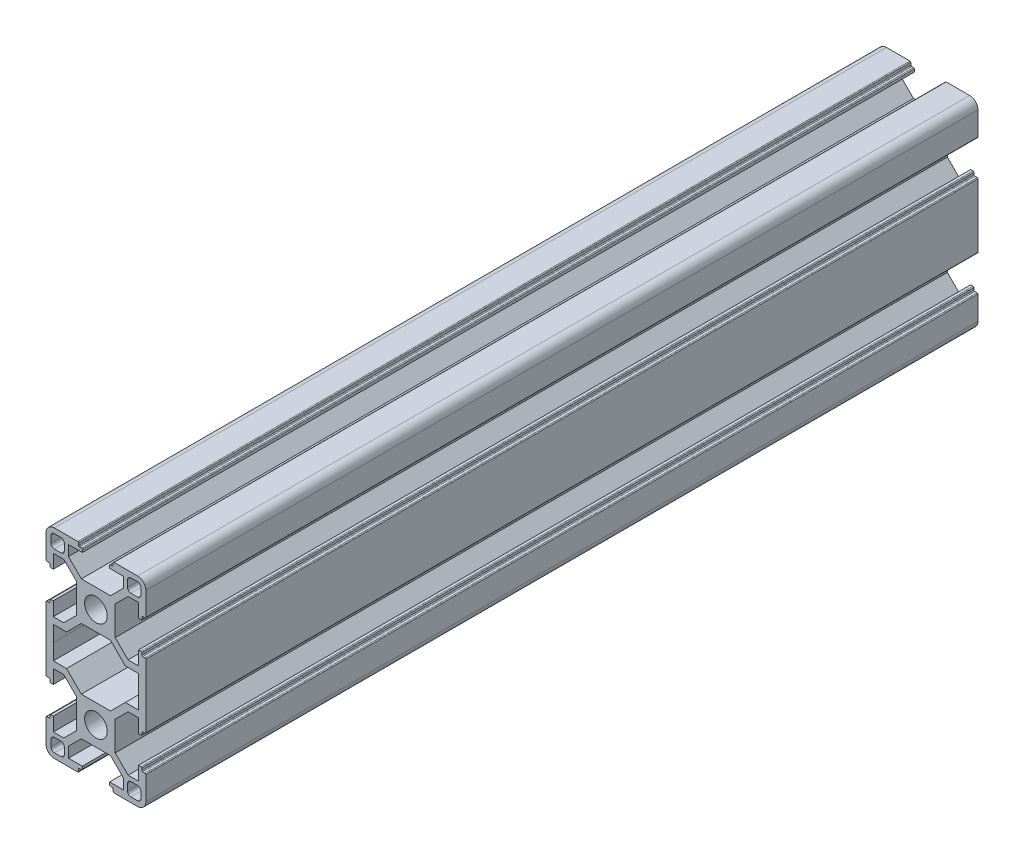
SolidWorks part; units mm, degrees
ref_plane "Front Plane" through (0, 0, 0) normal (0, 0, 1) x (1, 0, 0)
ref_plane "Top Plane" through (0, 0, 0) normal (0, 1, 0) x (1, 0, 0)
ref_plane "Right Plane" through (0, 0, 0) normal (1, 0, 0) x (0, 0, -1)
sketch "Sketch1" plane through (0, 0, 0) normal (0, 0, 1) x (1, 0, 0)
  line L0 (0, -5.8) -> (0, 5.8) construction
  line L1 (0, 0) -> (-15, 15) construction
  line L2 (-15, 15) -> (-5.2, 15)
  line L3 (-5.2, 15) -> (-5.2, 13.8083)
  line L4 (-5.2, 13.8083) -> (-4.1, 13.8083)
  line L5 (-4.1, 13.8083) -> (-4.1, 12.8)
  line L6 (-4.1, 12.8) -> (-8.25, 12.8)
  line L7 (-8.25, 12.8) -> (-8.25, 9.6642)
  line L8 (-8.25, 9.6642) -> (-4.3858, 5.8)
  line L9 (-4.3858, 5.8) -> (4.3858, 5.8)
  line L10 (-5.8, 4.3858) -> (-5.8, -4.3858)
  line L11 (-9.6642, 8.25) -> (-5.8, 4.3858)
  line L12 (-12.8, 8.25) -> (-9.6642, 8.25)
  line L13 (-12.8, 4.1) -> (-12.8, 8.25)
  line L14 (-13.8083, 4.1) -> (-12.8, 4.1)
  line L15 (-13.8083, 5.2) -> (-13.8083, 4.1)
  line L16 (-15, 5.2) -> (-13.8083, 5.2)
  line L17 (-15, 15) -> (-15, 5.2)
  line L18 (0, 0) -> (15, 15) construction
  line L19 (15, 15) -> (15, 5.2)
  line L20 (15, 5.2) -> (13.8083, 5.2)
  line L21 (13.8083, 5.2) -> (13.8083, 4.1)
  line L22 (13.8083, 4.1) -> (12.8, 4.1)
  line L23 (12.8, 4.1) -> (12.8, 8.25)
  line L24 (12.8, 8.25) -> (9.6642, 8.25)
  line L25 (9.6642, 8.25) -> (5.8, 4.3858)
  line L26 (5.8, 4.3858) -> (5.8, -4.3858)
  line L27 (8.25, 9.6642) -> (4.3858, 5.8)
  line L28 (8.25, 12.8) -> (8.25, 9.6642)
  line L29 (4.1, 12.8) -> (8.25, 12.8)
  line L30 (4.1, 13.8083) -> (4.1, 12.8)
  line L31 (5.2, 13.8083) -> (4.1, 13.8083)
  line L32 (5.2, 15) -> (5.2, 13.8083)
  line L33 (15, 15) -> (5.2, 15)
  line L34 (0, 0) -> (3.5826, 0) construction
  line L35 (0, 0) -> (15, -15) construction
  line L36 (0, 0) -> (-15, -15) construction
  line L37 (-4.3858, -5.8) -> (-8.8358, -10.25)
  line L38 (-8.8358, -10.25) -> (-12.8, -10.25)
  line L39 (-12.8, -10.25) -> (-12.7618, -15)
  line L40 (-12.8, -19.75) -> (-12.7618, -15)
  line L41 (-8.8358, -19.75) -> (-12.8, -19.75)
  line L42 (-4.3858, -24.2) -> (-8.8358, -19.75)
  line L43 (4.3858, -5.8) -> (8.8358, -10.25)
  line L44 (9.6642, -8.25) -> (5.8, -4.3858)
  line L45 (12.8, -8.25) -> (9.6642, -8.25)
  line L46 (12.8, -4.1) -> (12.8, -8.25)
  line L47 (13.8083, -4.1) -> (12.8, -4.1)
  line L48 (13.8083, -5.2) -> (13.8083, -4.1)
  line L49 (15, -5.2) -> (13.8083, -5.2)
  line L50 (15, -24.8) -> (15, -5.2)
  line L51 (-15, -24.8) -> (-15, -5.2)
  line L52 (-15, -5.2) -> (-13.8083, -5.2)
  line L53 (-13.8083, -5.2) -> (-13.8083, -4.1)
  line L54 (-13.8083, -4.1) -> (-12.8, -4.1)
  line L55 (-12.8, -4.1) -> (-12.8, -8.25)
  line L56 (-12.8, -8.25) -> (-9.6642, -8.25)
  line L57 (-9.6642, -8.25) -> (-5.8, -4.3858)
  line L58 (-4.3858, -5.8) -> (4.3858, -5.8)
  line L59 (8.8358, -10.25) -> (12.8, -10.25)
  line L60 (12.8, -10.25) -> (12.7618, -15)
  line L61 (12.8, -19.75) -> (12.7618, -15)
  line L62 (8.8358, -19.75) -> (12.8, -19.75)
  line L63 (4.3858, -24.2) -> (8.8358, -19.75)
  line L66 (0, -5.8) -> (0, -24.2) construction
  line L67 (0, -15) -> (-25.5237, -15) construction
  line L68 (0, -30) -> (-15, -15) construction
  line L69 (0, -30) -> (15, -15) construction
  line L70 (0, -30) -> (3.5826, -30) construction
  line L71 (0, -30) -> (15, -45) construction
  line L72 (0, -30) -> (-15, -45) construction
  line L73 (0, -24.2) -> (0, -35.8) construction
  line L79 (-4.3858, -24.2) -> (4.3858, -24.2)
  line L80 (-9.6642, -21.75) -> (-5.8, -25.6142)
  line L81 (-12.8, -21.75) -> (-9.6642, -21.75)
  line L82 (-12.8, -25.9) -> (-12.8, -21.75)
  line L83 (-13.8083, -25.9) -> (-12.8, -25.9)
  line L84 (-13.8083, -24.8) -> (-13.8083, -25.9)
  line L85 (-15, -24.8) -> (-13.8083, -24.8)
  line L86 (15, -24.8) -> (13.8083, -24.8)
  line L87 (13.8083, -24.8) -> (13.8083, -25.9)
  line L88 (13.8083, -25.9) -> (12.8, -25.9)
  line L89 (12.8, -25.9) -> (12.8, -21.75)
  line L90 (12.8, -21.75) -> (9.6642, -21.75)
  line L91 (9.6642, -21.75) -> (5.8, -25.6142)
  line L97 (15, -45) -> (5.2, -45)
  line L98 (5.2, -45) -> (5.2, -43.8083)
  line L99 (5.2, -43.8083) -> (4.1, -43.8083)
  line L100 (4.1, -43.8083) -> (4.1, -42.8)
  line L101 (4.1, -42.8) -> (8.25, -42.8)
  line L102 (8.25, -42.8) -> (8.25, -39.6642)
  line L103 (8.25, -39.6642) -> (4.3858, -35.8)
  line L104 (5.8, -34.3858) -> (5.8, -25.6142)
  line L105 (9.6642, -38.25) -> (5.8, -34.3858)
  line L106 (12.8, -38.25) -> (9.6642, -38.25)
  line L107 (12.8, -34.1) -> (12.8, -38.25)
  line L108 (13.8083, -34.1) -> (12.8, -34.1)
  line L109 (13.8083, -35.2) -> (13.8083, -34.1)
  line L110 (15, -35.2) -> (13.8083, -35.2)
  line L111 (15, -45) -> (15, -35.2)
  line L112 (-15, -45) -> (-15, -35.2)
  line L113 (-15, -35.2) -> (-13.8083, -35.2)
  line L114 (-13.8083, -35.2) -> (-13.8083, -34.1)
  line L115 (-13.8083, -34.1) -> (-12.8, -34.1)
  line L116 (-12.8, -34.1) -> (-12.8, -38.25)
  line L117 (-12.8, -38.25) -> (-9.6642, -38.25)
  line L118 (-9.6642, -38.25) -> (-5.8, -34.3858)
  line L119 (-5.8, -34.3858) -> (-5.8, -25.6142)
  line L120 (-4.3858, -35.8) -> (4.3858, -35.8)
  line L121 (-8.25, -39.6642) -> (-4.3858, -35.8)
  line L122 (-8.25, -42.8) -> (-8.25, -39.6642)
  line L123 (-4.1, -42.8) -> (-8.25, -42.8)
  line L124 (-4.1, -43.8083) -> (-4.1, -42.8)
  line L125 (-5.2, -43.8083) -> (-4.1, -43.8083)
  line L126 (-5.2, -45) -> (-5.2, -43.8083)
  line L127 (-15, -45) -> (-5.2, -45)
  point P30 (0, 5.8)
  point P48 (5.8, 0)
  point P61 (-5.8, 0)
  point P130 (-5.8, -30)
  point P131 (5.8, -30)
  dimension "D1" = 2
  dimension "D2" = 15
  dimension "D3" = 1
  dimension "D4" = 4.1
  dimension "D5" = 5.2
  dimension "D6" = 2.2
  dimension "D7" = 8.25
  dimension "D8" = 9.2
extrude "Boss-Extrude1" add sketch "Sketch1" along normal blind 250
sketch "Sketch2" plane through (0, 0, 250) normal (0, 0, 1) x (1, 0, 0)
  line L0 (0, 0) -> (0, 17.0054) construction
  line L1 (0, 0) -> (20.7717, 0) construction
  line L2 (-5.2, 15) -> (-15, 15) construction
  line L3 (-12.5, 13.5) -> (-10.5, 13.5)
  line L4 (-13.5, 12.5) -> (-13.5, 10.5)
  line L5 (-12.5, 9.5) -> (-10.5, 9.5)
  line L6 (-9.5, 12.5) -> (-9.5, 10.5)
  line L7 (-13.5, 13.5) -> (-9.5, 9.5) construction
  line L8 (-13.5, 9.5) -> (-9.5, 13.5) construction
  line L9 (-15, 15) -> (-15, 5.2) construction
  line L10 (13.5, 9.5) -> (9.5, 13.5) construction
  line L11 (13.5, 13.5) -> (9.5, 9.5) construction
  line L12 (9.5, 12.5) -> (9.5, 10.5)
  line L13 (12.5, 9.5) -> (10.5, 9.5)
  line L14 (13.5, 12.5) -> (13.5, 10.5)
  line L15 (12.5, 13.5) -> (10.5, 13.5)
  line L16 (13.5, -43.5) -> (9.5, -39.5) construction
  line L17 (13.5, -39.5) -> (9.5, -43.5) construction
  line L18 (-13.5, -39.5) -> (-9.5, -43.5) construction
  line L19 (-13.5, -43.5) -> (-9.5, -39.5) construction
  line L20 (0, -30) -> (20.7717, -30) construction
  line L21 (0, -30) -> (0, -47.0054) construction
  line L22 (12.5, -43.5) -> (10.5, -43.5)
  line L23 (13.5, -42.5) -> (13.5, -40.5)
  line L24 (12.5, -39.5) -> (10.5, -39.5)
  line L25 (9.5, -42.5) -> (9.5, -40.5)
  line L26 (-9.5, -42.5) -> (-9.5, -40.5)
  line L27 (-12.5, -39.5) -> (-10.5, -39.5)
  line L28 (-12.7618, -15) -> (12.7618, -15) construction
  line L29 (-13.5, -42.5) -> (-13.5, -40.5)
  line L30 (-12.5, -43.5) -> (-10.5, -43.5)
  arc A0 (-12.5, 13.5) -> (-13.5, 12.5) centre (-12.5, 12.5) ccw
  arc A1 (-13.5, 10.5) -> (-12.5, 9.5) centre (-12.5, 10.5) ccw
  arc A2 (-10.5, 9.5) -> (-9.5, 10.5) centre (-10.5, 10.5) ccw
  arc A3 (-10.5, 13.5) -> (-9.5, 12.5) centre (-10.5, 12.5) cw
  arc A4 (10.5, 13.5) -> (9.5, 12.5) centre (10.5, 12.5) ccw
  arc A5 (10.5, 9.5) -> (9.5, 10.5) centre (10.5, 10.5) cw
  arc A6 (13.5, 10.5) -> (12.5, 9.5) centre (12.5, 10.5) cw
  arc A7 (12.5, 13.5) -> (13.5, 12.5) centre (12.5, 12.5) cw
  circle A8 centre (0, -30) radius 3.4
  arc A9 (12.5, -43.5) -> (13.5, -42.5) centre (12.5, -42.5) ccw
  arc A10 (13.5, -40.5) -> (12.5, -39.5) centre (12.5, -40.5) ccw
  arc A11 (10.5, -39.5) -> (9.5, -40.5) centre (10.5, -40.5) ccw
  arc A12 (10.5, -43.5) -> (9.5, -42.5) centre (10.5, -42.5) cw
  arc A13 (-10.5, -43.5) -> (-9.5, -42.5) centre (-10.5, -42.5) ccw
  arc A14 (-10.5, -39.5) -> (-9.5, -40.5) centre (-10.5, -40.5) cw
  arc A15 (-13.5, -40.5) -> (-12.5, -39.5) centre (-12.5, -40.5) cw
  circle A16 centre (0, 0) radius 3.4
  arc A17 (-12.5, -43.5) -> (-13.5, -42.5) centre (-12.5, -42.5) cw
  point P3 (-11.5, 11.5)
  point P41 (11.5, 11.5)
  point P83 (11.5, -41.5)
  point P84 (-11.5, -41.5)
  dimension "D5" = 1
  dimension "D6" = 6.8
  dimension "D1" = 1.5
  dimension "D2" = 1.5
  dimension "D3" = 4
  dimension "D4" = 4
extrude "Cut-Extrude1" cut sketch "Sketch2" against normal through all
fillet "Fillet1" radius 2.5 4 edges at (15, 15, 125) (-15, 15, 125) (-15, -45, 125) (15, -45, 125)
fillet "Fillet2" radius 0.25 36 edges at (-13.8083, 5.2, 125) (-13.8083, 4.1, 125) (-15, 5.2, 125) (-13.8083, -4.1, 125) (-13.8083, -5.2, 125) (-15, -5.2, 125) (13.8083, -5.2, 125) (13.8083, -4.1, 125) (15, -5.2, 125) (13.8083, 4.1, 125) (13.8083, 5.2, 125) (15, 5.2, 125) (-4.1, 13.8083, 125) (-5.2, 13.8083, 125) (4.1, 13.8083, 125) (5.2, 13.8083, 125) (5.2, 15, 125) (-5.2, 15, 125) (-5.2, -45, 125) (-5.2, -43.8083, 125) (-4.1, -43.8083, 125) (5.2, -45, 125) (5.2, -43.8083, 125) (4.1, -43.8083, 125) (15, -35.2, 125) (13.8083, -35.2, 125) (13.8083, -34.1, 125) (13.8083, -25.9, 125) (13.8083, -24.8, 125) (15, -24.8, 125) (-15, -35.2, 125) (-13.8083, -35.2, 125) (-13.8083, -34.1, 125) (-13.8083, -25.9, 125) (-13.8083, -24.8, 125) (-15, -24.8, 125)
